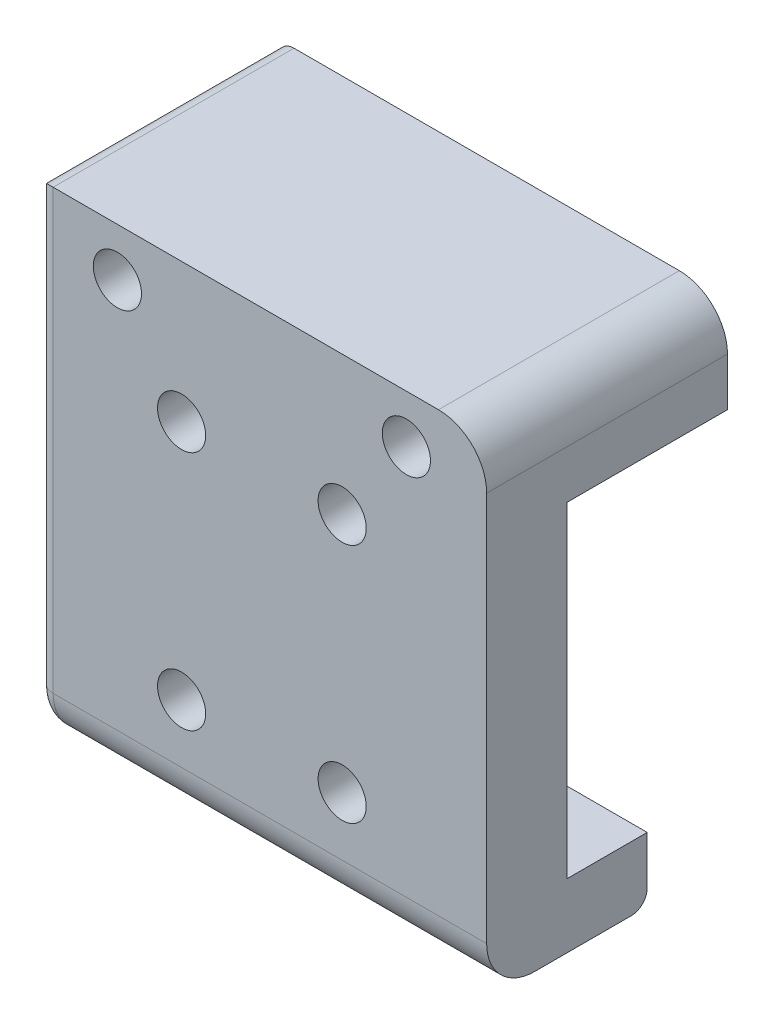
SolidWorks part; units mm, degrees
ref_plane "前视基准面" through (0, 0, 0) normal (0, 0, 1) x (1, 0, 0)
ref_plane "上视基准面" through (0, 0, 0) normal (0, 1, 0) x (1, 0, 0)
ref_plane "右视基准面" through (0, 0, 0) normal (1, 0, 0) x (0, 0, -1)
other "Configuration Table"
sketch "草图1" plane through (0, 0, 0) normal (0, 0, 1) x (1, 0, 0)
  line L1 (-5, 7.5) -> (5, 7.5) construction
  line L2 (-5, 7.5) -> (-5, -7.5) construction
  line L3 (-5, -7.5) -> (5, -7.5) construction
  line L4 (5, 7.5) -> (5, -7.5) construction
  line L5 (-5, 7.5) -> (5, -7.5) construction
  line L6 (-5, -7.5) -> (5, 7.5) construction
  line L7 (-14, 10.15) -> (14, 10.15)
  line L8 (-14, 10.15) -> (-14, -10.15)
  line L9 (-14, -10.15) -> (14, -10.15)
  line L10 (14, 10.15) -> (14, -10.15)
  line L11 (-14, 10.15) -> (14, -10.15) construction
  line L12 (-14, -10.15) -> (14, 10.15) construction
  circle A0 centre (-5, 7.5) radius 1.5
  circle A1 centre (5, 7.5) radius 1.5
  circle A2 centre (5, -7.5) radius 1.5
  circle A3 centre (-5, -7.5) radius 1.5
  point P0 (0, 0)
  point P6 (0, 0)
  dimension "D4" = 3
  dimension "D1" = 15
  dimension "D2" = 10
  dimension "D3" = 28
  dimension "D5" = 20.3
extrude "凸台-拉伸1" add sketch "草图1" along normal blind 5
sketch "草图2" plane through (0, 0, 5) normal (0, 0, 1) x (1, 0, 0)
  line L0 (-14, 0) -> (14, 0)
  line L1 (14, 10.15) -> (-14, 10.15)
  line L2 (-14, -10.15) -> (14, -10.15)
  line L3 (-14, -10.15) -> (-14, -14.15)
  line L4 (14, -10.15) -> (14, 10.15)
  line L5 (14, 10.15) -> (-14, 10.15)
  line L6 (-14, 10.15) -> (-14, -10.15)
  line L7 (-14, -10.15) -> (14, -10.15)
  line L8 (14, -10.15) -> (14, 10.15)
  line L9 (14, 10.15) -> (-14, 10.15)
  line L10 (-14, 10.15) -> (-14, -10.15)
  line L11 (-14, -10.15) -> (14, -10.15)
  line L12 (-14, -14.15) -> (14, -14.15)
  line L13 (14, -10.15) -> (14, -14.15)
  line L14 (14, 10.15) -> (14, 16.15)
  line L15 (-14, 10.15) -> (-14, 16.15)
  line L16 (14, 16.15) -> (-14, 16.15)
  line M11 (14, 10.15) -> (-14, 10.15)
  line M13 (-14, -10.15) -> (14, -10.15)
  dimension "D2" = 4
  dimension "D3" = 6
  dimension "D1" = 0
extrude "凸台-拉伸2" add sketch "草图2" against normal blind 10 contours L14 L16 L15 L1 M11 | L13 L3 L12 M13
sketch "草图3" plane through (0, 0, -5) normal (0, 0, -1) x (-1, 0, 0)
  line L4 (-14, 16.15) -> (-14, 10.15)
  line L5 (-14, 10.15) -> (14, 10.15)
  line L6 (14, 10.15) -> (14, 16.15)
  line L7 (14, 16.15) -> (-14, 16.15)
  line L8 (-14, 16.15) -> (-14, 10.15)
  line L9 (-14, 10.15) -> (14, 10.15)
  line L10 (14, 10.15) -> (14, 16.15)
  line L11 (14, 16.15) -> (-14, 16.15)
  dimension "D1" = 0
extrude "凸台-拉伸3" add sketch "草图3" along normal blind 5
fillet "圆角1" radius 3 2 edges at (0, -14.15, 5) (14, 16.15, -2.5)
fillet "圆角2" radius 1 5 edges at (0, -14.15, -5) (-14, 2.5, 5) (-14, -13.2713, 4.1213) (-14, 16.15, -2.5) (-14, -14.15, -1.5)
sketch "草图4" plane through (0, 0, 5) normal (0, 0, 1) x (1, 0, 0)
  line L0 (11, 16.15) -> (-13, 16.15) construction
  line L1 (-13, 16.15) -> (-13, -11.15) construction
  circle A0 centre (-9, 13.15) radius 1.5
  circle A1 centre (0, 13.15) radius 1.5 construction
  circle A2 centre (9, 13.15) radius 1.5
  dimension "D1" = 3
  dimension "D2" = 3
  dimension "D3" = 4
  dimension "D5" = 9
  dimension "D4" = 3
extrude "切除-拉伸1" cut sketch "草图4" against normal through all
